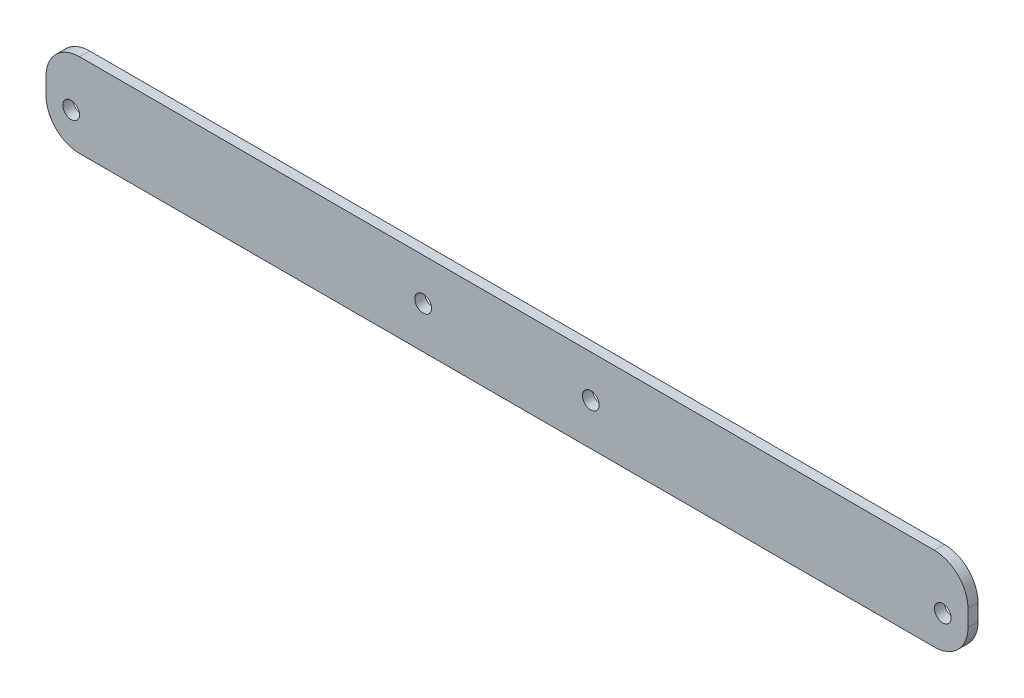
SolidWorks part; units mm, degrees
ref_plane "Front Plane" through (0, 0, 0) normal (0, 0, 1) x (1, 0, 0)
ref_plane "Top Plane" through (0, 0, 0) normal (0, 1, 0) x (1, 0, 0)
ref_plane "Right Plane" through (0, 0, 0) normal (1, 0, 0) x (0, 0, -1)
sketch "Sketch1" plane through (0, 0, 0) normal (0, 0, 1) x (1, 0, 0)
  line L1 (10, 0) -> (265, 0)
  line L2 (0, 10) -> (0, 15)
  line L3 (10, 25) -> (265, 25)
  line L4 (275, 10) -> (275, 15)
  circle A0 centre (267.5, 10) radius 2.5
  circle A1 centre (7.5, 10) radius 2.5
  arc A2 (10, 0) -> (0, 10) centre (10, 10) cw
  arc A3 (0, 15) -> (10, 25) centre (10, 15) cw
  arc A4 (265, 0) -> (275, 10) centre (265, 10) ccw
  arc A5 (265, 25) -> (275, 15) centre (265, 15) cw
  circle A6 centre (112.5, 12.5) radius 2.5
  circle A7 centre (162.5, 12.5) radius 2.5
  point P11 (0, 0)
  point P14 (0, 25)
  point P19 (275, 25)
  point P24 (137.5, 0)
  dimension "D3" = 5
  dimension "D4" = 7.5
  dimension "D5" = 15
  dimension "D6" = 15
  dimension "D7" = 7.5
  dimension "D8" = 5
  dimension "D9" = 10
  dimension "D10" = 5
  dimension "D11" = 5
  dimension "D12" = 12.5
  dimension "D13" = 12.5
  dimension "D14" = 50
  dimension "D1" = 275
  dimension "D2" = 25
  dimension "D15" = 25
extrude "Boss-Extrude1" add sketch "Sketch1" along normal blind 3
